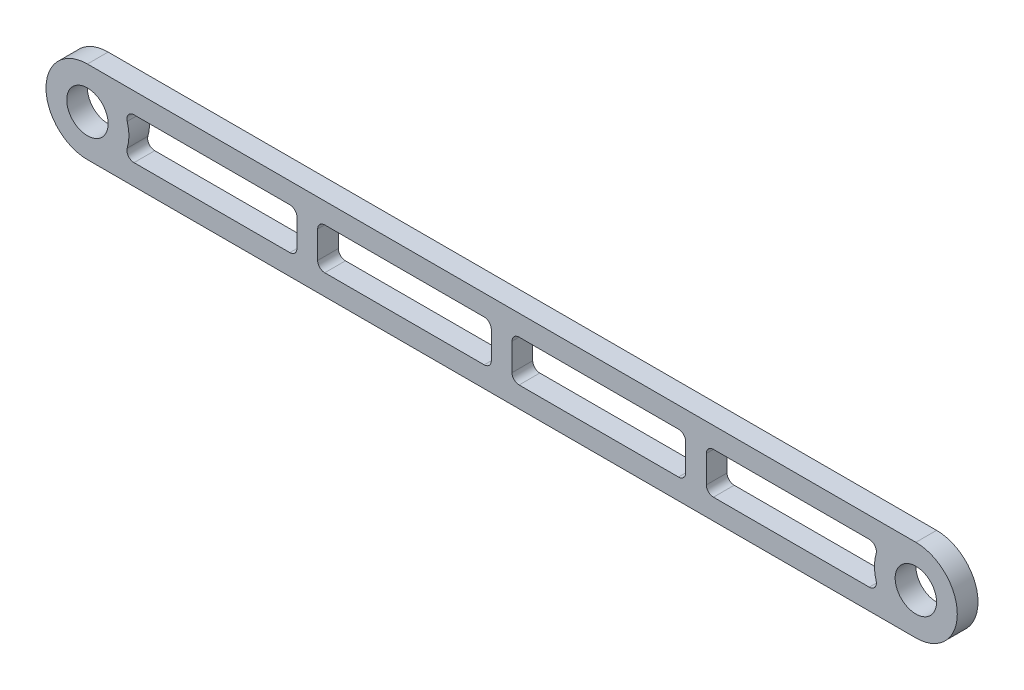
SolidWorks part; units mm, degrees
ref_plane "Front" through (0, 0, 0) normal (0, 0, 1) x (1, 0, 0)
ref_plane "Top" through (0, 0, 0) normal (0, 1, 0) x (1, 0, 0)
ref_plane "Right" through (0, 0, 0) normal (1, 0, 0) x (0, 0, -1)
sketch "草图1" plane through (0, 0, 0) normal (0, 0, 1) x (1, 0, 0)
  line L0 (0, 0) -> (200, 0) construction
  line L1 (0, 10) -> (200, 10)
  line L2 (0, -10) -> (200, -10)
  line L3 (11.2454, 5) -> (48.8648, 5)
  line L4 (188.7546, -5) -> (151.1352, -5)
  line L5 (104.2153, 5) -> (142.7045, 5)
  line L6 (102.5, 0) -> (102.5, 3.2847)
  line L7 (95.7847, -5) -> (57.2955, -5)
  line L8 (97.5, 0) -> (97.5, 3.2847)
  line L9 (97.5, 0) -> (97.5, -3.2847)
  line L10 (102.5, 0) -> (102.5, -3.2847)
  line L11 (57.2955, 5) -> (95.7847, 5)
  line L12 (151.1352, 5) -> (188.7546, 5)
  line L13 (55.5801, 0) -> (55.5801, 3.2847)
  line L14 (142.7045, -5) -> (104.2153, -5)
  line L15 (50.5801, 0) -> (50.5801, 3.2847)
  line L16 (50.5801, 0) -> (50.5801, -3.2847)
  line L17 (55.5801, 0) -> (55.5801, -3.2847)
  line L18 (48.8648, -5) -> (11.2454, -5)
  line L19 (149.4199, 0) -> (149.4199, 3.2847)
  line L21 (144.4199, 0) -> (144.4199, 3.2847)
  line L22 (144.4199, 0) -> (144.4199, -3.2847)
  line L23 (149.4199, 0) -> (149.4199, -3.2847)
  arc A0 (0, 10) -> (0, -10) centre (0, 0) ccw
  arc A1 (200, -10) -> (200, 10) centre (200, 0) ccw
  circle A2 centre (0, 0) radius 5
  circle A3 centre (200, 0) radius 5
  arc A4 (9.5989, 2.8037) -> (9.5989, -2.8037) centre (0, 0) cw
  arc A5 (190.4011, 2.8037) -> (190.4011, -2.8037) centre (200, 0) ccw
  arc A6 (11.2454, -5) -> (9.5989, -2.8037) centre (11.2454, -3.2847) cw
  arc A7 (11.2454, 5) -> (9.5989, 2.8037) centre (11.2454, 3.2847) ccw
  arc A8 (48.8648, 5) -> (50.5801, 3.2847) centre (48.8648, 3.2847) cw
  arc A9 (48.8648, -5) -> (50.5801, -3.2847) centre (48.8648, -3.2847) ccw
  arc A10 (57.2955, -5) -> (55.5801, -3.2847) centre (57.2955, -3.2847) cw
  arc A11 (57.2955, 5) -> (55.5801, 3.2847) centre (57.2955, 3.2847) ccw
  arc A12 (95.7847, -5) -> (97.5, -3.2847) centre (95.7847, -3.2847) ccw
  arc A13 (97.5, 3.2847) -> (95.7847, 5) centre (95.7847, 3.2847) ccw
  arc A14 (188.7546, 5) -> (190.4011, 2.8037) centre (188.7546, 3.2847) cw
  arc A15 (188.7546, -5) -> (190.4011, -2.8037) centre (188.7546, -3.2847) ccw
  arc A16 (151.1352, -5) -> (149.4199, -3.2847) centre (151.1352, -3.2847) cw
  arc A17 (149.4199, 3.2847) -> (151.1352, 5) centre (151.1352, 3.2847) cw
  arc A18 (142.7045, 5) -> (144.4199, 3.2847) centre (142.7045, 3.2847) cw
  arc A19 (142.7045, -5) -> (144.4199, -3.2847) centre (142.7045, -3.2847) ccw
  arc A20 (104.2153, -5) -> (102.5, -3.2847) centre (104.2153, -3.2847) cw
  arc A21 (104.2153, 5) -> (102.5, 3.2847) centre (104.2153, 3.2847) ccw
  point P3 (100, 0)
  point P44 (50.5801, -5)
  point P49 (55.5801, 5)
  point P52 (97.5, -5)
  point P63 (149.4199, 5)
  point P68 (144.4199, -5)
  point P73 (102.5, 5)
  dimension "D1" = 10
  dimension "D3" = 10
  dimension "D4" = 10
  dimension "D5" = 5
  dimension "D7" = 1.7153
  dimension "D2" = 200
  dimension "D6" = 5
extrude "凸台-拉伸1" add sketch "草图1" along normal blind 5
